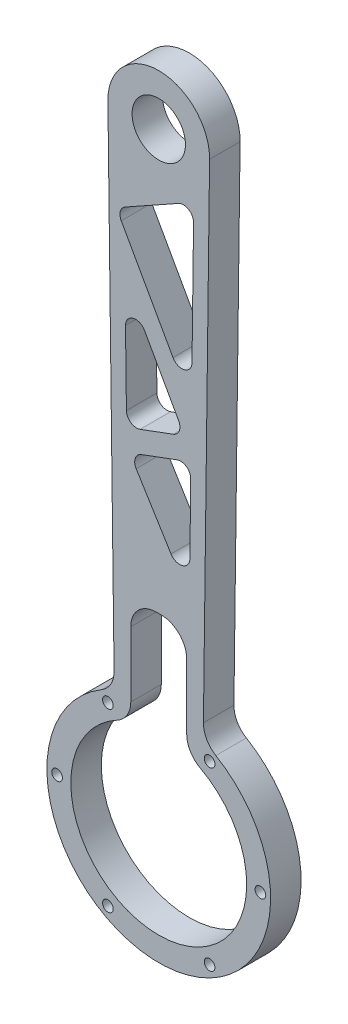
SolidWorks part; units mm, degrees
material "Thornel Mat VMA"
ref_plane "前视基准面" through (0, 0, 0) normal (0, 0, 1) x (1, 0, 0)
ref_plane "上视基准面" through (0, 0, 0) normal (0, 1, 0) x (1, 0, 0)
ref_plane "右视基准面" through (0, 0, 0) normal (1, 0, 0) x (0, 0, -1)
other "Configuration Table"
sketch "草图1" plane through (0, 0, 0) normal (0, 0, 1) x (1, 0, 0)
  line L0 (0, 0) -> (0, 240) construction
  line L1 (-17.5, 40.3702) -> (-19.9984, 239.7494)
  line L2 (-17.5, 40.3702) -> (17.5, 40.3702) construction
  line L3 (17.5, 40.3702) -> (19.9984, 239.7494)
  arc A0 (-17.5, 40.3702) -> (17.5, 40.3702) centre (0, 0) ccw
  arc A9 (19.9984, 239.7494) -> (-19.9984, 239.7494) centre (0, 240) ccw
  point P19 (0, 0)
  dimension "D1" = 240
  dimension "D2" = 88
  dimension "D7" = 40
  dimension "D8" = 35
extrude "凸台-拉伸1" add sketch "草图1" along normal blind 12
sketch "草图2" plane through (0, 0, 12) normal (0, 0, 1) x (1, 0, 0)
  line L0 (0, 40) -> (0, 0) construction
  line L1 (0, 0) -> (20, 34.641) construction
  circle A0 centre (0, 240) radius 10.5
  circle A1 centre (0, 0) radius 40 construction
  circle A2 centre (0, 0) radius 34.6
  circle A3 centre (20, 34.641) radius 2.1
  circle A4 centre (40, 0) radius 2.1
  circle A5 centre (20, -34.641) radius 2.1
  circle A6 centre (-20, -34.641) radius 2.1
  circle A7 centre (-40, 0) radius 2.1
  circle A8 centre (-20, 34.641) radius 2.1
  point P21 (0, 0)
  dimension "D1" = 21
  dimension "D2" = 69.2
  dimension "D3" = 80
  dimension "D4" = 4.2
  dimension "D6" = 30
  dimension "D5" = 6
extrude "切除-拉伸1" cut sketch "草图2" against normal blind 12
fillet "圆角1" radius 10 2 edges at (17.5, 40.3702, 6) (-17.5, 40.3702, 6)
sketch "草图3" plane through (0, 0, 0) normal (0, 0, -1) x (-1, 0, 0)
  line L0 (0, 0) -> (0, 97.5588) construction
  line L1 (-11, 25) -> (11, 25)
  line L2 (-11, 25) -> (-11, 75)
  line L3 (-11, 75) -> (11, 75)
  line L4 (11, 25) -> (11, 75)
  dimension "D1" = 22
  dimension "D2" = 11
  dimension "D3" = 50
  dimension "D4" = 25
extrude "切除-拉伸2" cut sketch "草图3" against normal blind 12
fillet "圆角2" radius 10 4 edges at (-11, 75, 6) (-11, 32.8049, 6) (11, 75, 6) (11, 32.8049, 6)
sketch "草图5" plane through (0, 0, 0) normal (0, 0, -1) x (-1, 0, 0)
  line L0 (-13.775, 221.9579) -> (16.706, 204.9335)
  line L1 (16.706, 204.9335) -> (-12.8975, 151.9306)
  line L2 (-12.8975, 151.9306) -> (-13.775, 221.9579)
  line L3 (13.2792, 182.392) -> (-10.0841, 140.5616)
  line L4 (-10.0841, 140.5616) -> (12.6491, 132.1076)
  line L5 (12.6491, 132.1076) -> (13.2792, 182.392)
  line L6 (-12.6601, 132.9843) -> (11.4319, 124.025)
  line L7 (11.4319, 124.025) -> (-12.0715, 86.0184)
  line L8 (-12.0715, 86.0184) -> (-12.6601, 132.9843)
  line L9 (-17.5775, 46.5529) -> (-19.9984, 239.7494) construction
  line L10 (19.9984, 239.7494) -> (17.5775, 46.5529) construction
  dimension "D1" = 6
  dimension "D2" = 8
  dimension "D3" = 6
  dimension "D4" = 8
  dimension "D5" = 6
extrude "切除-拉伸3" cut sketch "草图5" against normal through all
fillet "圆角4" radius 4 9 edges at (-16.706, 204.9335, 6) (12.8975, 151.9306, 6) (12.6601, 132.9843, 6) (-11.4319, 124.025, 6) (12.0715, 86.0184, 6) (-12.6491, 132.1076, 6) (10.0841, 140.5616, 6) (-13.2792, 182.392, 6) (13.775, 221.9579, 6)
